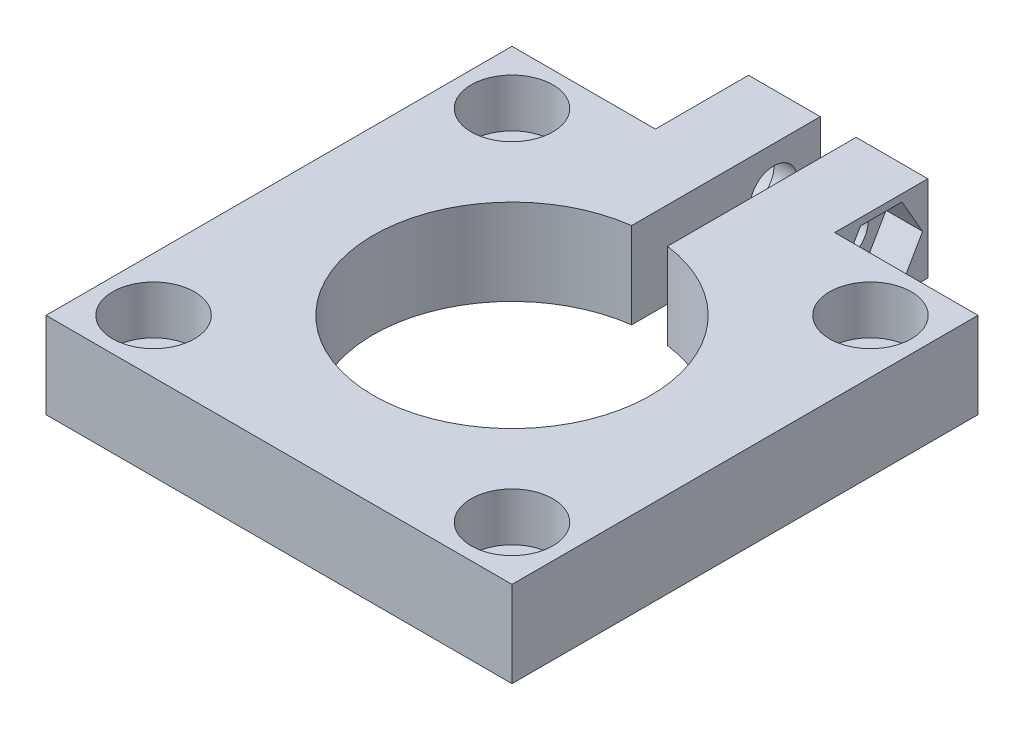
SolidWorks part; units mm, degrees
ref_plane "Front Plane" through (0, 0, 0) normal (0, 0, 1) x (1, 0, 0)
ref_plane "Top Plane" through (0, 0, 0) normal (0, 1, 0) x (1, 0, 0)
ref_plane "Right Plane" through (0, 0, 0) normal (1, 0, 0) x (0, 0, -1)
sketch "Sketch1" plane through (0, 0, 0) normal (0, 1, 0) x (1, 0, 0)
  line L1 (-32.5, 32.5) -> (32.5, 32.5)
  line L2 (-32.5, 32.5) -> (-32.5, -32.5)
  line L3 (-32.5, -32.5) -> (32.5, -32.5)
  line L4 (32.5, 32.5) -> (32.5, -32.5)
  line L5 (-32.5, 32.5) -> (32.5, -32.5) construction
  line L6 (-32.5, -32.5) -> (32.5, 32.5) construction
  point P0 (0, 0)
  dimension "D1" = 65
  dimension "D2" = 65
extrude "Boss-Extrude1" add sketch "Sketch1" along normal blind 12
sketch "Sketch3" plane through (0, 12, 0) normal (0, 1, 0) x (-1, 0, 0)
  circle A0 centre (0, 0) radius 19.35
  dimension "D1" = 38.7
extrude "Cut-Extrude1" cut sketch "Sketch3" against normal blind 12
sketch "Sketch4" plane through (0, 12, 0) normal (0, 1, 0) x (-1, 0, 0)
  line L0 (-32.5, -32.5) -> (32.5, -32.5) construction
  line L1 (2.5, -52.5) -> (-2.5, -52.5)
  line L2 (2.5, -52.5) -> (2.5, -12.5)
  line L3 (2.5, -12.5) -> (-2.5, -12.5)
  line L4 (-2.5, -52.5) -> (-2.5, -12.5)
  line L5 (2.5, -52.5) -> (-2.5, -12.5) construction
  line L6 (2.5, -12.5) -> (-2.5, -52.5) construction
  point P0 (0, -32.5)
  dimension "D1" = 40
extrude "Cut-Extrude2" cut sketch "Sketch4" against normal blind 12
sketch "Sketch5" plane through (0, 12, 0) normal (0, 1, 0) x (-1, 0, 0)
  line L1 (2.5, -32.5) -> (12.5, -32.5)
  line L2 (2.5, -32.5) -> (2.5, -45.5)
  line L3 (2.5, -45.5) -> (12.5, -45.5)
  line L4 (12.5, -32.5) -> (12.5, -45.5)
  dimension "D1" = 13
  dimension "D2" = 10
extrude "Boss-Extrude4" add sketch "Sketch5" against normal blind 12
pattern_linear "LPattern1" count 2 spacing 15 along (1, 0, 0) of "Boss-Extrude4"
hole_wizard "CBORE for M6 Hex Socket Head Cap Screw1" positions "Sketch7" profile "Sketch6" counterbore size "M6" standard "DIN" end condition through all
sketch "Sketch7" plane through (-12.5, 0, 0) normal (-1, 0, 0) x (0, 0, 1)
  line L0 (-45.5, 0) -> (-32.5, 0) construction
  line L1 (-45.5, 0) -> (-45.5, 12) construction
  point P0 (-39, 6)
  point P10 (-39, 0)
  point P11 (-45.5, 6)
  dimension "D1" = 0
  dimension "D2" = 0
sketch "Sketch6" plane through (-12.5, 6, -39) normal (0, 1, 0) x (0, 0, 1)
  line L0 (0, 0) -> (0, 45)
  line L1 (0, 45) -> (3.3, 45)
  line L3 (3.3, 45) -> (3.3, 6.75)
  line L4 (3.3, 6.75) -> (5.25, 6.75)
  line L5 (5.25, 6.75) -> (5.25, 0)
  line L7 (5.25, 0) -> (0, 0)
  line L11 (0, -6.35) -> (0, 107.95) construction
  dimension "Thru Hole Dia." = 6.6
  dimension "Thru Hole Depth" = 45
  dimension "C'Bore Dia." = 10.5
  dimension "C'Bore Depth" = 6.75
sketch "Sketch9" plane through (12.5, 0, 0) normal (1, 0, 0) x (0, 0, -1)
  line L0 (32.5, 0) -> (45.5, 0) construction
  line L1 (44.7735, 6) -> (41.8868, 11)
  line L2 (41.8868, 11) -> (36.1132, 11)
  line L3 (36.1132, 11) -> (33.2265, 6)
  line L4 (33.2265, 6) -> (36.1132, 1)
  line L5 (36.1132, 1) -> (41.8868, 1)
  line L6 (41.8868, 1) -> (44.7735, 6)
  line L8 (45.5, 0) -> (45.5, 12) construction
  circle A0 centre (39, 6) radius 5 construction
  point P1 (39, 0)
  point P11 (45.5, 6)
  dimension "D1" = 5
  dimension "D2" = 0
  dimension "D3" = 0
extrude "Cut-Extrude3" cut sketch "Sketch9" against normal blind 5.1
hole_wizard "CBORE for M6 Hex Socket Head Cap Screw2" positions "Sketch11" profile "Sketch10" counterbore size "M6" standard "DIN" end condition through all
sketch "Sketch11" plane through (0, 12, 0) normal (0, 1, 0) x (-1, 0, 0)
  point P0 (25, -25)
  dimension "D1" = 25
  dimension "D2" = 25
sketch "Sketch10" plane through (-25, 12, -25) normal (1, 0, 0) x (0, 0, 1)
  line L0 (0, 0) -> (0, 12)
  line L1 (0, 12) -> (3.75, 12)
  line L3 (3.75, 12) -> (3.75, 6.75)
  line L4 (3.75, 6.75) -> (5.7, 6.75)
  line L5 (5.7, 6.75) -> (5.7, 0)
  line L7 (5.7, 0) -> (0, 0)
  line L11 (0, -6.35) -> (0, 107.95) construction
  dimension "Thru Hole Dia." = 7.5
  dimension "Thru Hole Depth" = 12
  dimension "C'Bore Dia." = 11.4
  dimension "C'Bore Depth" = 6.75
hole_wizard "CBORE for M6 Hex Socket Head Cap Screw3" positions "Sketch13" profile "Sketch12" counterbore size "M6" standard "DIN" end condition through all
sketch "Sketch13" plane through (0, 12, 0) normal (0, 1, 0) x (-1, 0, 0)
  point P0 (-25, -25)
  dimension "D1" = 25
  dimension "D2" = 25
sketch "Sketch12" plane through (25, 12, -25) normal (1, 0, 0) x (0, 0, 1)
  line L0 (0, 0) -> (0, 12)
  line L1 (0, 12) -> (3.75, 12)
  line L3 (3.75, 12) -> (3.75, 6.75)
  line L4 (3.75, 6.75) -> (5.7, 6.75)
  line L5 (5.7, 6.75) -> (5.7, 0)
  line L7 (5.7, 0) -> (0, 0)
  line L11 (0, -6.35) -> (0, 107.95) construction
  dimension "Thru Hole Dia." = 7.5
  dimension "Thru Hole Depth" = 12
  dimension "C'Bore Dia." = 11.4
  dimension "C'Bore Depth" = 6.75
hole_wizard "CBORE for M6 Hex Socket Head Cap Screw4" positions "Sketch15" profile "Sketch14" counterbore size "M6" standard "DIN" end condition through all
sketch "Sketch15" plane through (0, 12, 0) normal (0, 1, 0) x (-1, 0, 0)
  point P0 (-25, 25)
  dimension "D1" = 25
  dimension "D2" = 25
sketch "Sketch14" plane through (25, 12, 25) normal (1, 0, 0) x (0, 0, 1)
  line L0 (0, 0) -> (0, 12)
  line L1 (0, 12) -> (3.75, 12)
  line L3 (3.75, 12) -> (3.75, 6.75)
  line L4 (3.75, 6.75) -> (5.7, 6.75)
  line L5 (5.7, 6.75) -> (5.7, 0)
  line L7 (5.7, 0) -> (0, 0)
  line L11 (0, -6.35) -> (0, 107.95) construction
  dimension "Thru Hole Dia." = 7.5
  dimension "Thru Hole Depth" = 12
  dimension "C'Bore Dia." = 11.4
  dimension "C'Bore Depth" = 6.75
hole_wizard "CBORE for M6 Hex Socket Head Cap Screw5" positions "Sketch17" profile "Sketch16" counterbore size "M6" standard "DIN" end condition through all
sketch "Sketch17" plane through (0, 12, 0) normal (0, 1, 0) x (-1, 0, 0)
  point P0 (25, 25)
  dimension "D1" = 25
  dimension "D2" = 25
sketch "Sketch16" plane through (-25, 12, 25) normal (1, 0, 0) x (0, 0, 1)
  line L0 (0, 0) -> (0, 12)
  line L1 (0, 12) -> (3.75, 12)
  line L3 (3.75, 12) -> (3.75, 6.75)
  line L4 (3.75, 6.75) -> (5.7, 6.75)
  line L5 (5.7, 6.75) -> (5.7, 0)
  line L7 (5.7, 0) -> (0, 0)
  line L11 (0, -6.35) -> (0, 107.95) construction
  dimension "Thru Hole Dia." = 7.5
  dimension "Thru Hole Depth" = 12
  dimension "C'Bore Dia." = 11.4
  dimension "C'Bore Depth" = 6.75
